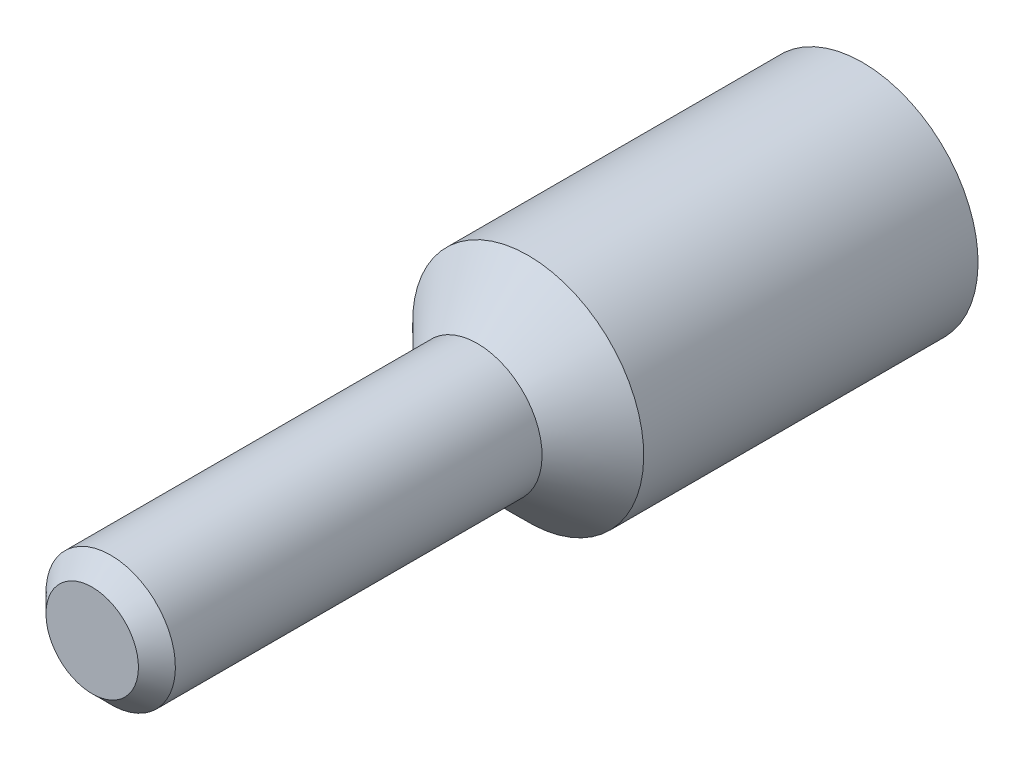
SolidWorks part; units mm, degrees
ref_plane "Plan de face" through (0, 0, 0) normal (0, 0, 1) x (1, 0, 0)
ref_plane "Plan de dessus" through (0, 0, 0) normal (0, 1, 0) x (1, 0, 0)
ref_plane "Plan de droite" through (0, 0, 0) normal (1, 0, 0) x (0, 0, -1)
sketch "Esquisse1" plane through (0, 0, 0) normal (1, 0, 0) x (0, 0, -1)
  line L0 (36.9, 0) -> (-13.1, 0)
  line L1 (-13.1, 0) -> (-13.1, 3)
  line L3 (-11.9, 4.2) -> (11.9, 4.2)
  line L5 (15.2, 7.5) -> (36.9, 7.5)
  line L6 (36.9, 7.5) -> (36.9, 0)
  line L8 (11.9, 4.2) -> (15.2, 7.5)
  line L9 (-11.9, 4.2) -> (-13.1, 3)
  line L10 (0, 16.1679) -> (0, -16.7731) construction
  point P4 (0, 4.2)
  point P7 (0, 0)
  point P9 (0, 0)
  point P10 (0, 0)
  dimension "D1" = 7.5
  dimension "D2" = 25
  dimension "D3" = 4.2
  dimension "D4" = 50
  dimension "D5" = 3
  dimension "D6" = 135
  dimension "D7" = 135
revolve "Révolution1" add sketch "Esquisse1" angle 360 about L0
